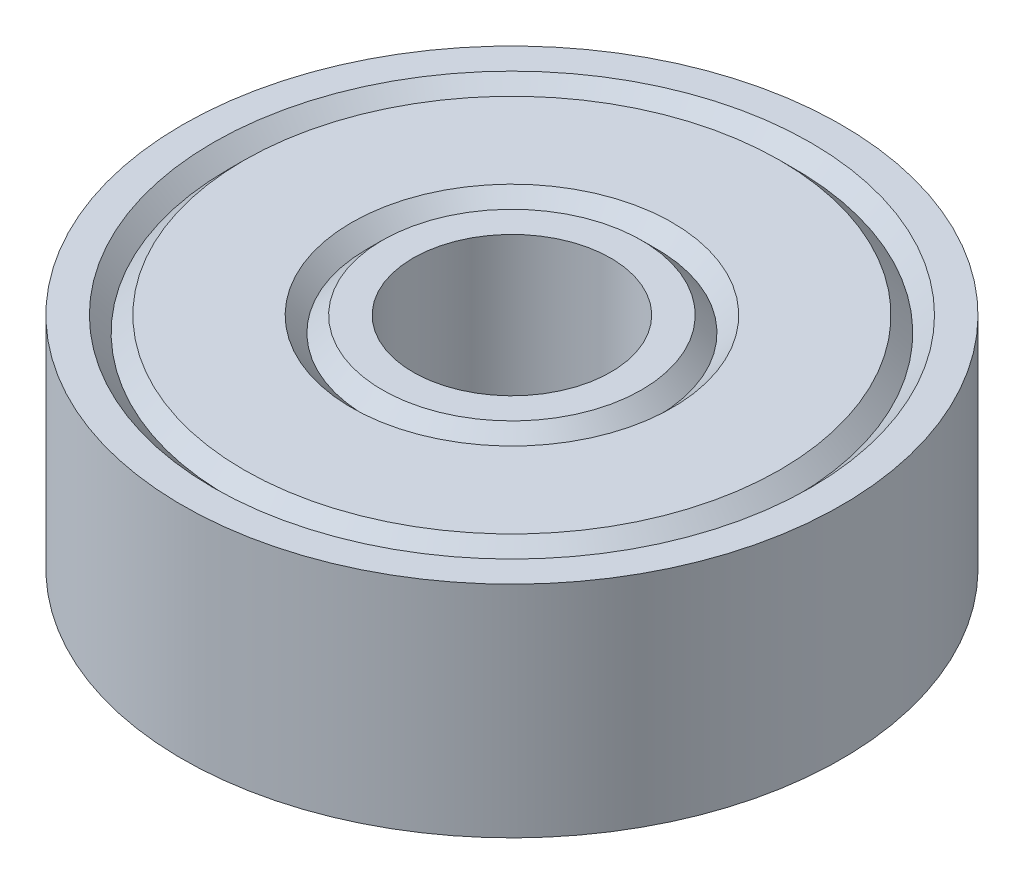
SolidWorks part; units mm, degrees
ref_plane "Front Plane" through (0, 0, 0) normal (0, 0, 1) x (1, 0, 0)
ref_plane "Top Plane" through (0, 0, 0) normal (0, 1, 0) x (1, 0, 0)
ref_plane "Right Plane" through (0, 0, 0) normal (1, 0, 0) x (0, 0, -1)
sketch "Sketch1" plane through (0, 0, 0) normal (0, 0, 1) x (1, 0, 0)
  line L0 (0, 5) -> (0, -5) construction
  line L1 (-4.5, 5) -> (-5.9, 5)
  line L2 (-4.5, 5) -> (-4.5, -5)
  line L3 (-4.5, -5) -> (-5.9, -5)
  line L4 (-15, 5) -> (-15, -5)
  line L5 (-13.6, 5) -> (-12.9, 4.3)
  line L6 (-12.9, 4.3) -> (-12.2, 5)
  line L7 (-7.3, 5) -> (-6.6, 4.3)
  line L8 (-6.6, 4.3) -> (-5.9, 5)
  line L9 (-13.6, -5) -> (-12.9, -4.3)
  line L10 (-12.9, -4.3) -> (-12.2, -5)
  line L11 (-7.3, -5) -> (-6.6, -4.3)
  line L12 (-6.6, -4.3) -> (-5.9, -5)
  line L13 (-7.3, -5) -> (-12.2, -5)
  line L14 (-13.6, -5) -> (-15, -5)
  line L15 (-13.6, 5) -> (-15, 5)
  line L16 (-7.3, 5) -> (-12.2, 5)
  line L17 (-12.9, 4.3) -> (-6.6, 4.3) construction
  line L18 (-12.9, 4.3) -> (-12.9, -4.3) construction
  line L19 (-6.6, -4.3) -> (-12.9, -4.3) construction
  line L20 (-6.6, 4.3) -> (-6.6, -4.3) construction
  line L21 (-12.9, 0) -> (-10.8, 0) construction
  line L22 (-5.9, 5) -> (-7.3, 5) construction
  line L23 (-10.8, 0) -> (-8.7, 0) construction
  line L24 (-12.9, 0) -> (-15, 0) construction
  line L25 (-8.7, 0) -> (-6.6, 0) construction
  line L26 (-6.6, 0) -> (-4.5, 0) construction
  dimension "D1" = 10
  dimension "D2" = 9
  dimension "D3" = 30
revolve "Revolve1" add sketch "Sketch1" angle 360 about L0
